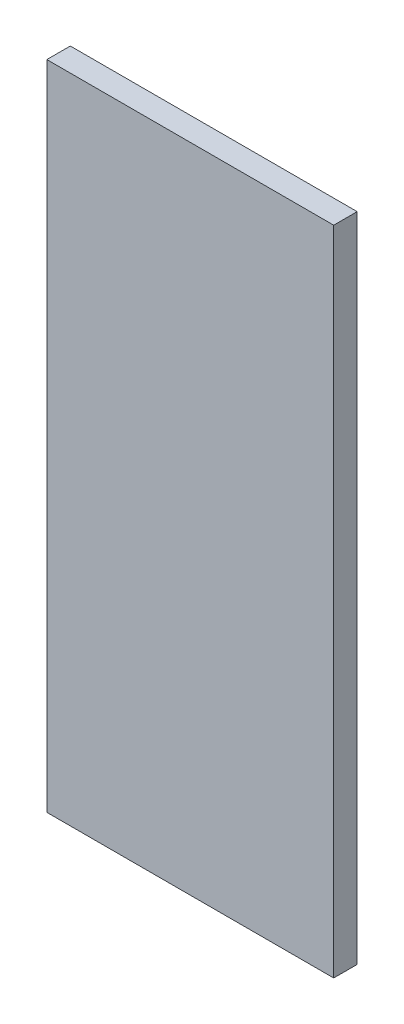
SolidWorks part; units mm, degrees
ref_plane "Front Plane" through (0, 0, 0) normal (0, 0, 1) x (1, 0, 0)
ref_plane "Top Plane" through (0, 0, 0) normal (0, 1, 0) x (1, 0, 0)
ref_plane "Right Plane" through (0, 0, 0) normal (1, 0, 0) x (0, 0, -1)
sketch "Sketch1" plane through (0, 0, 0) normal (0, 0, 1) x (1, 0, 0)
  line L1 (-110, -250) -> (110, -250)
  line L2 (-110, -250) -> (-110, 250)
  line L3 (-110, 250) -> (110, 250)
  line L4 (110, -250) -> (110, 250)
  line L5 (-110, -250) -> (110, 250) construction
  line L6 (-110, 250) -> (110, -250) construction
  point P0 (0, 0)
  dimension "D1" = 220
  dimension "D2" = 500
extrude "Boss-Extrude1" add sketch "Sketch1" along normal blind 18
